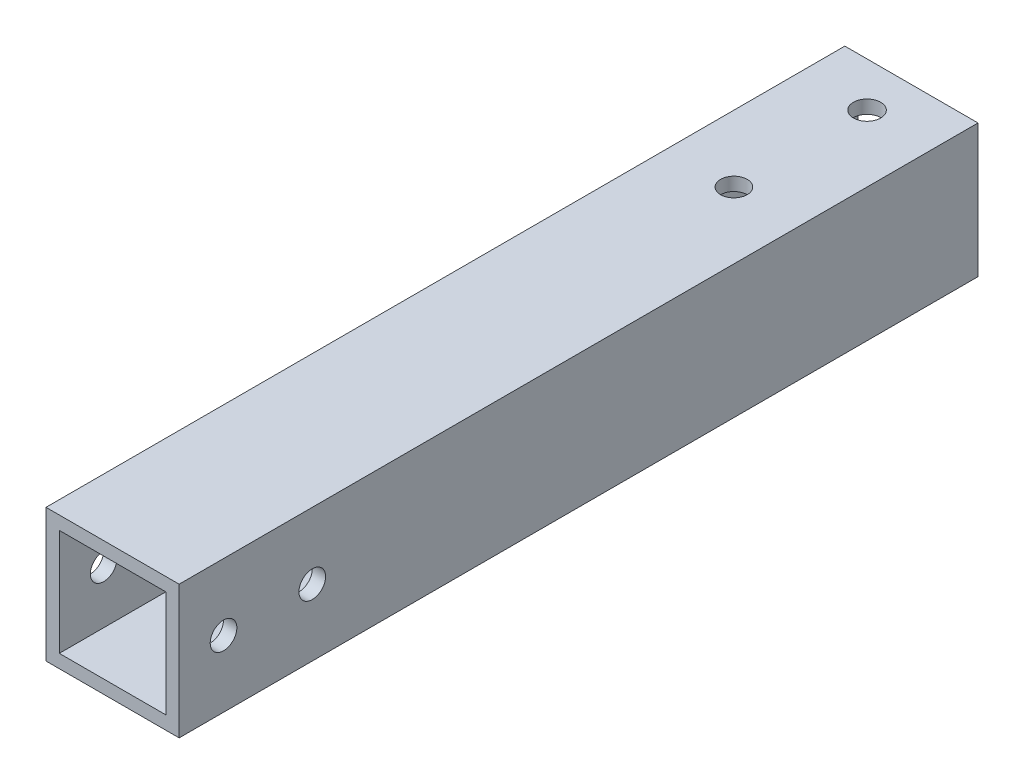
SolidWorks part; units mm, degrees
ref_plane "Plan de face" through (0, 0, 0) normal (0, 0, 1) x (1, 0, 0)
ref_plane "Plan de dessus" through (0, 0, 0) normal (0, 1, 0) x (1, 0, 0)
ref_plane "Plan de droite" through (0, 0, 0) normal (1, 0, 0) x (0, 0, -1)
sketch "Esquisse1" plane through (0, 0, 0) normal (0, 0, 1) x (1, 0, 0)
  line L1 (-7.5, -7.5) -> (7.5, -7.5)
  line L2 (-7.5, -7.5) -> (-7.5, 7.5)
  line L3 (-7.5, 7.5) -> (7.5, 7.5)
  line L4 (7.5, -7.5) -> (7.5, 7.5)
  line L5 (-7.5, -7.5) -> (7.5, 7.5) construction
  line L6 (-7.5, 7.5) -> (7.5, -7.5) construction
  point P0 (0, 0)
  dimension "D1" = 15
  dimension "D2" = 15
extrude "Extrusion1" add sketch "Esquisse1" along normal blind 90
sketch "Esquisse2" plane through (0, 0, 90) normal (0, 0, 1) x (1, 0, 0)
  line L0 (7.5, 7.5) -> (-7.5, 7.5) construction
  line L1 (-6, -6) -> (6, -6)
  line L2 (-6, -6) -> (-6, 6)
  line L3 (-6, 6) -> (6, 6)
  line L4 (6, -6) -> (6, 6)
  line L5 (-6, -6) -> (6, 6) construction
  line L6 (-6, 6) -> (6, -6) construction
  line L7 (7.5, -7.5) -> (7.5, 7.5) construction
  point P0 (0, 0)
  dimension "D1" = 1.5
  dimension "D2" = 1.5
extrude "Extrusion2" cut sketch "Esquisse2" against normal through all
sketch "Esquisse3" plane through (7.5, 0, 0) normal (1, 0, 0) x (0, 0, -1)
  circle A0 centre (-85, 0) radius 1.5
  circle A1 centre (-75, 0) radius 1.5
extrude "Enlèv. mat.-Extru.1" cut sketch "Esquisse3" against normal through all
sketch "Esquisse4" plane through (0, 7.5, 0) normal (0, 1, 0) x (1, 0, 0)
  circle A0 centre (0, -20) radius 1.5
  circle A1 centre (0, -5) radius 1.5388
extrude "Enlèv. mat.-Extru.2" cut sketch "Esquisse4" against normal through all
sketch "Esquisse5" plane through (-7.5, 0, 0) normal (-1, 0, 0) x (0, 0, 1)
  line L0 (0, 7.5) -> (0, -7.5) construction
  line L1 (90, 7.5) -> (0, 7.5) construction
  circle A0 centre (7.5, 0) radius 4
  dimension "D2" = 7.5
  dimension "D3" = 8
  dimension "D1" = 7.5
extrude "Enlèv. mat.-Extru.3" [suppressed] cut sketch "Esquisse5" against normal blind 2
